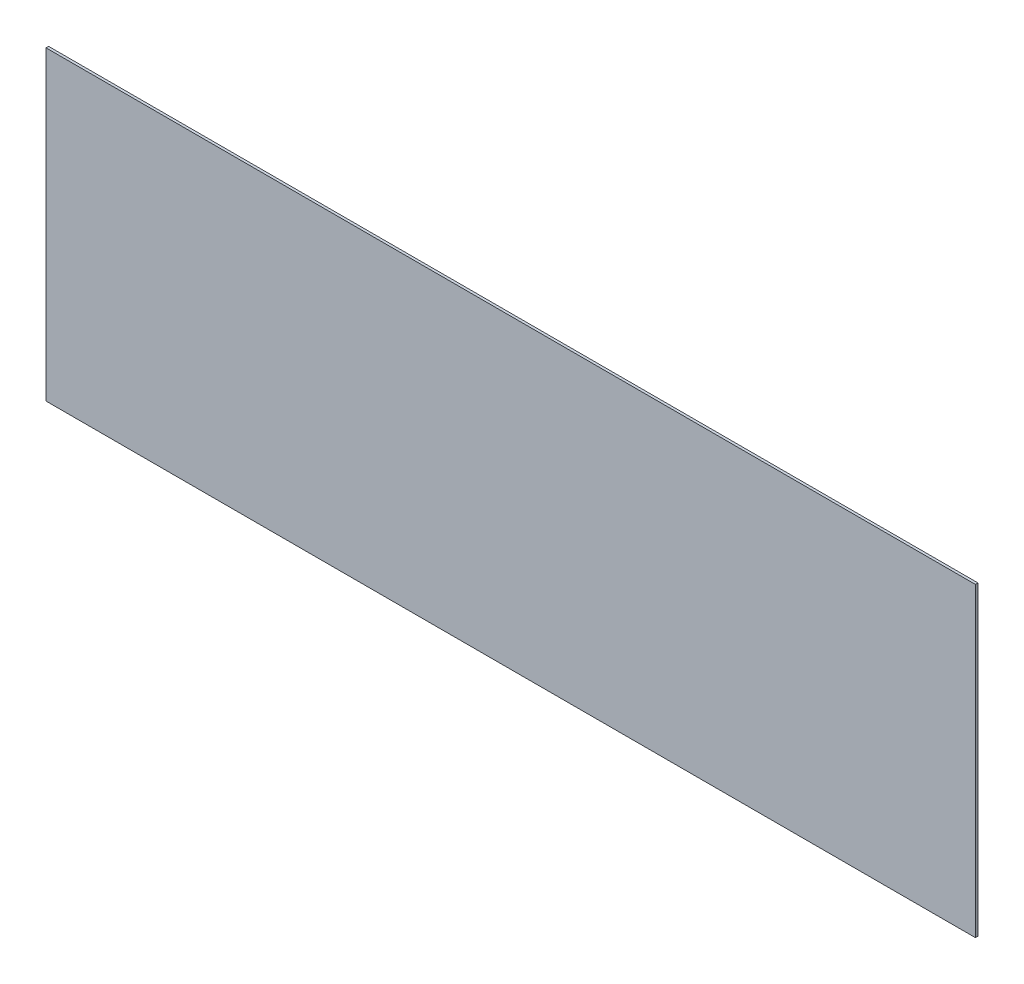
SolidWorks part; units mm, degrees
ref_plane "前视基准面" through (0, 0, 0) normal (0, 0, 1) x (1, 0, 0)
ref_plane "上视基准面" through (0, 0, 0) normal (0, 1, 0) x (1, 0, 0)
ref_plane "右视基准面" through (0, 0, 0) normal (1, 0, 0) x (0, 0, -1)
sketch "草图1" plane through (0, 0, 0) normal (0, 0, 1) x (1, 0, 0)
  line L1 (-10, 156.5) -> (-370, 156.5)
  line L2 (-10, 156.5) -> (-10, 275)
  line L3 (-10, 275) -> (-370, 275)
  line L4 (-370, 156.5) -> (-370, 275)
extrude "凸台-拉伸1" add sketch "草图1" against normal blind 1
sketch "草图2" plane through (0, 0, 0) normal (0, 0, 1) x (1, 0, 0)
  line L0 (-970.2009, 436.4629) -> (-313.5342, 436.4629) construction
